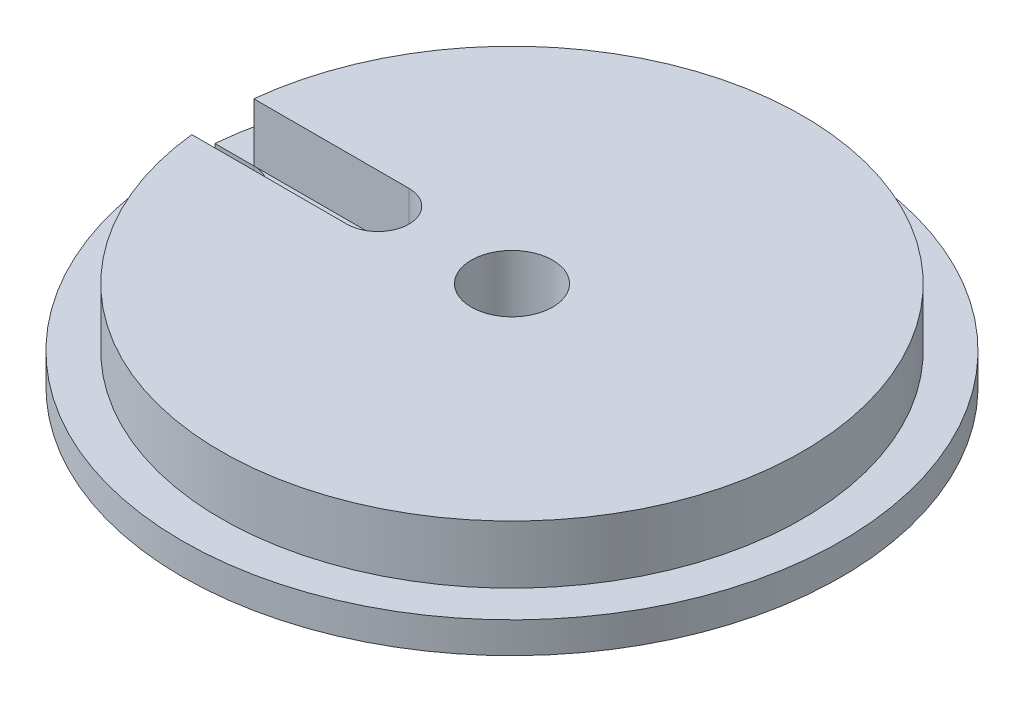
SolidWorks part; units mm, degrees
material "ABS"
ref_plane "正面" through (0, 0, 0) normal (0, 0, 1) x (1, 0, 0)
ref_plane "平面" through (0, 0, 0) normal (0, 1, 0) x (1, 0, 0)
ref_plane "右側面" through (0, 0, 0) normal (1, 0, 0) x (0, 0, -1)
sketch "ｽｹｯﾁ1" plane through (0, 0, 0) normal (0, 1, 0) x (1, 0, 0)
  circle A0 centre (0, 0) radius 2.1
  circle A1 centre (0, 0) radius 15
  dimension "D1" = 30
  dimension "D2" = 4.2
extrude "ﾎﾞｽ - 押し出し1" add sketch "ｽｹｯﾁ1" along normal blind 3
sketch "ｽｹｯﾁ2" plane through (0, 3, 0) normal (0, 1, 0) x (1, 0, 0)
  line L1 (-14.9144, 1.6) -> (-6.9144, 1.6)
  line L2 (-14.9144, 1.6) -> (-14.9144, -1.6) construction
  line L3 (-14.9144, -1.6) -> (-6.9144, -1.6)
  line L4 (-6.9144, 1.6) -> (-6.9144, -1.6) construction
  circle A0 centre (0, 0) radius 15 construction
  arc A1 (-6.9144, 1.6) -> (-6.9144, -1.6) centre (-6.9144, 0) cw
  arc A2 (-14.9144, 1.6) -> (-14.9144, -1.6) centre (-14.9144, 0) ccw
  dimension "D1" = 3.2
  dimension "D2" = 8
extrude "ｶｯﾄ - 押し出し1" cut sketch "ｽｹｯﾁ2" against normal blind 10
sketch "ｽｹｯﾁ3" plane through (0, 0, 0) normal (0, -1, 0) x (1, 0, 0)
  line L0 (-16.9245, -1.6) -> (-14.9144, -1.6)
  line L2 (-14.9144, 1.6) -> (-16.9245, 1.6)
  arc A0 (-16.9245, -1.6) -> (-16.9245, 1.6) centre (0, 0) ccw
  circle A1 centre (-6.9144, 0) radius 1.6
  arc A2 (-6.9144, -1.6) -> (-6.9144, 1.6) centre (-6.9144, 0) ccw construction
  circle A3 centre (0, 0) radius 2.1 construction
  circle A4 centre (0, 0) radius 2.1
  arc A5 (-14.9144, 1.6) -> (-14.9144, -1.6) centre (-14.9144, 0) cw
  arc A6 (-16.9245, 1.6) -> (-16.9245, -1.6) centre (0, 0) ccw construction
  dimension "D1" = 34
extrude "ﾎﾞｽ - 押し出し2" add sketch "ｽｹｯﾁ3" along normal blind 1.6
